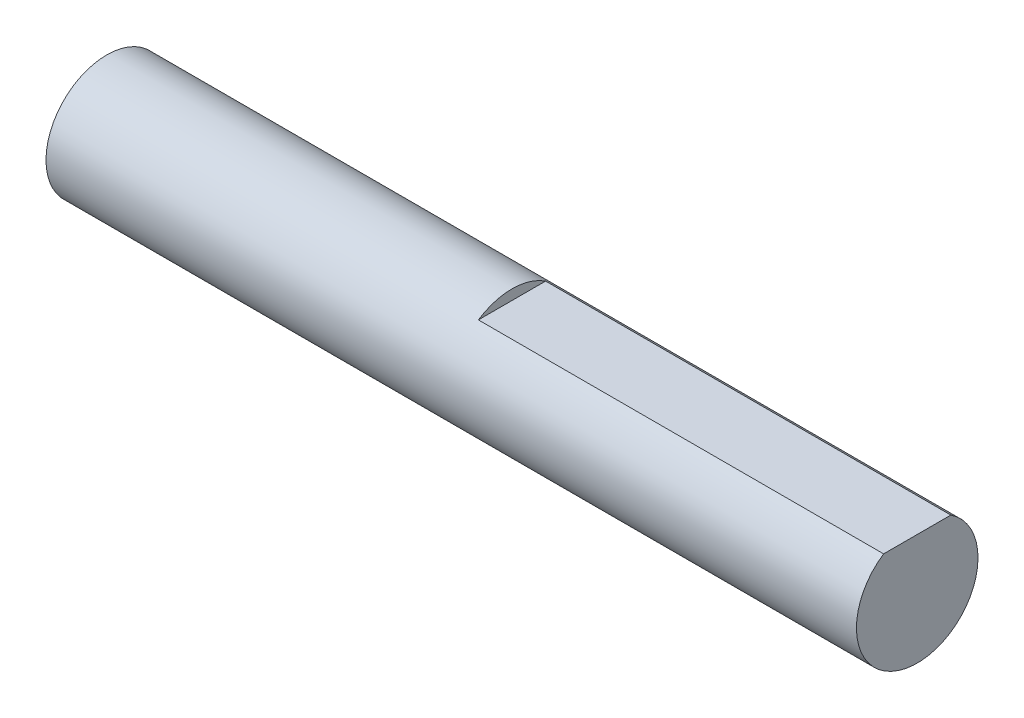
SolidWorks part; units mm, degrees
ref_plane "Front" through (0, 0, 0) normal (0, 0, 1) x (1, 0, 0)
ref_plane "Top" through (0, 0, 0) normal (0, 1, 0) x (1, 0, 0)
ref_plane "Right" through (0, 0, 0) normal (1, 0, 0) x (0, 0, -1)
sketch "Sketch1" plane through (0, 0, 0) normal (1, 0, 0) x (0, 0, -1)
  circle A0 centre (0, 0) radius 3
  dimension "D1" = 6
extrude "Boss-Extrude1" add sketch "Sketch1" along normal blind 40
ref_plane "Plane1" through (0, 3, 0) normal (0, 1, 0) x (1, 0, 0)
sketch "Sketch2" plane through (0, 3, 0) normal (0, 1, 0) x (1, 0, 0)
  line L0 (40, -3) -> (40, 3) construction
  line L1 (40, 5.9871) -> (20, 5.9871)
  line L2 (40, 5.9871) -> (40, -5.1645)
  line L3 (40, -5.1645) -> (20, -5.1645)
  line L4 (20, 5.9871) -> (20, -5.1645)
  dimension "D1" = 20
extrude "Cut-Extrude1" cut sketch "Sketch2" against normal blind 0.5
